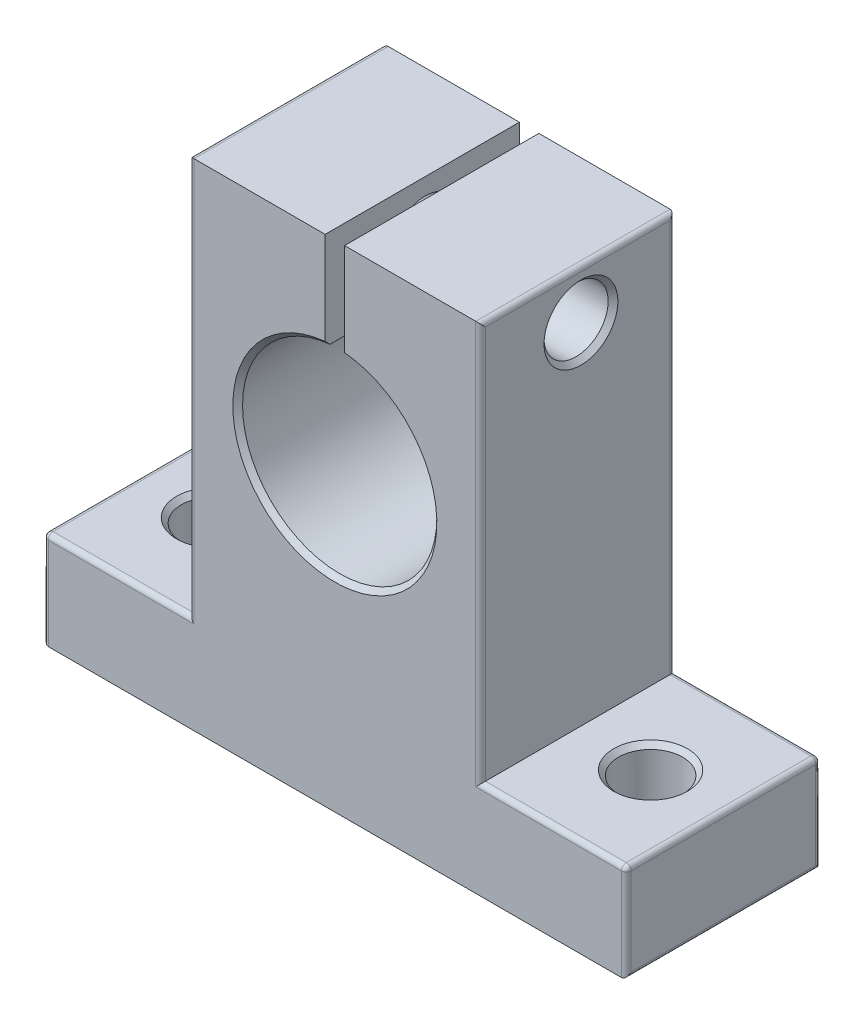
SolidWorks part; units mm, degrees
material "1060 Alloy"
ref_plane "Front Plane" through (0, 0, 0) normal (0, 0, 1) x (1, 0, 0)
ref_plane "Top Plane" through (0, 0, 0) normal (0, 1, 0) x (1, 0, 0)
ref_plane "Right Plane" through (0, 0, 0) normal (1, 0, 0) x (0, 0, -1)
sketch "Sketch1" plane through (0, 0, 0) normal (0, 0, 1) x (1, 0, 0)
  line L0 (0, 0) -> (-50000, 0) construction
  line L1 (0, 0) -> (0, 50000) construction
  line L2 (-30, -5) -> (-30, 5)
  line L3 (-30, 5) -> (-15, 5)
  line L4 (-15, 5) -> (-15, 46)
  line L5 (-15, 46) -> (-1, 46)
  line L6 (15, 46) -> (15, 5)
  line L7 (15, 5) -> (30, 5)
  line L8 (30, 5) -> (30, -5)
  line L9 (30, -5) -> (-30, -5)
  line L10 (22.5, -3) -> (22.5, 3) construction
  line L11 (-22.5, -3) -> (-22.5, 3) construction
  line L12 (-1, 46) -> (-1, 35.9499)
  line L13 (1, 46) -> (1, 35.9499)
  line L14 (1, 46) -> (15, 46)
  arc A0 (-1, 35.9499) -> (1, 35.9499) centre (0, 26) ccw
  point P8 (-30, 0)
  point P15 (0, -5)
  point P21 (22.5, 0)
  dimension "Shaft Diameter" = 20
  dimension "W" = 60
  dimension "P" = 30
  dimension "F" = 51
  dimension "G" = 10
  dimension "B" = 45
  dimension "D1" = 2
  dimension "h" = 31
extrude "Boss-Extrude1" add sketch "Sketch1" along normal mid plane 20
sketch "Sketch2" plane through (0, 5, 0) normal (0, 1, 0) x (1, 0, 0)
  line L0 (0, 0) -> (50000, 0) construction
  line L1 (0.3141, 0) -> (-49999.6859, 0) construction
  line L2 (0, 2.4842) -> (0, 50002.4842) construction
  circle A0 centre (22.5, 0) radius 3.3
  circle A1 centre (-22.5, 0) radius 3.3
  dimension "B" = 45
  dimension "S" = 6.6
extrude "Cut-Extrude1" cut sketch "Sketch2" against normal through all
sketch "Sketch5" plane through (-1, 0, 0) normal (1, 0, 0) x (0, 0, -1)
  line L0 (-10, 40.9749) -> (10, 40.9749) construction
  line L1 (10, 35.9499) -> (10, 46) construction
  line L2 (0, 46) -> (0, 35.9499) construction
  line L3 (-10, 46) -> (10, 46) construction
  line L4 (-10, 35.9499) -> (10, 35.9499) construction
  line L5 (-10, 35.9499) -> (-10, 46) construction
  circle A0 centre (0.3307, 40.9749) radius 3.3
  dimension "Clamping bold" = 6.6
extrude "Cut-Extrude2" cut sketch "Sketch5" against normal through all both and the other way through all
chamfer "Chamfer2" distance 0.5 angle 45 6 edges at (0, 16, -10) (0, 16, 10) (-15, 40.9749, -3.6307) (-19.2, 5, 0) (15, 40.9749, 2.9693) (19.2, 5, 0)
fillet "Fillet2" radius 0.5 18 edges at (30, -5, 0) (30, 0, 10) (30, 5, 0) (30, 0, -10) (-30, 0, 10) (-30, -5, 0) (-30, 0, -10) (-22.5, 5, -10) (-22.5, 5, 10) (-15, 25.5, 10) (-15, 46, 0) (-15, 25.5, -10) (15, 25.5, -10) (15, 25.5, 10) (22.5, 5, 10) (22.5, 5, -10) (15, 46, 0) (-30, 5, 0)
equation "\"W\"= \"W@Sketch1\"'Width"
equation "\"B\"= \"B@Sketch1\"'between hold"
equation "\"F\"= \"F@Sketch1\"'Hight"
equation "\"P\"= \"P@Sketch1\""
equation "\"G\"= \"G@Sketch1\""
equation "\"Shaft diameter\"= \"Shaft Diameter@Sketch1\""
equation "\"S\"= 6.6'M6"
equation "\"Clamping bold\"= 6.6'M6"
equation "\"h\"= \"h@Sketch1\""
